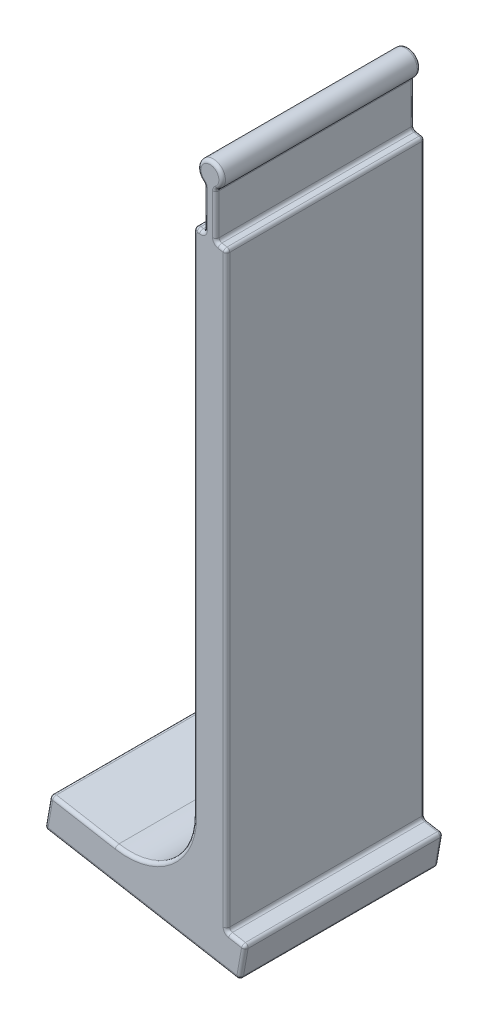
SolidWorks part; units mm, degrees
ref_plane "Alzado" through (0, 0, 0) normal (0, 0, 1) x (1, 0, 0)
ref_plane "Planta" through (0, 0, 0) normal (0, 1, 0) x (1, 0, 0)
ref_plane "Vista lateral" through (0, 0, 0) normal (1, 0, 0) x (0, 0, -1)
sketch "Croquis1" plane through (0, 0, 0) normal (0, 0, 1) x (1, 0, 0)
  line L0 (-0.9, 0) -> (0.9, 0)
  line L1 (-0.9, 0) -> (-0.9, -9.3)
  line L2 (0.9, 0) -> (0.9, -9.3)
  line L3 (-0.9, -9.3) -> (0.9, -9.3)
  line L16 (2.1527, -10.695) -> (-2.5, -9.8746)
  line L17 (2.1527, -10.695) -> (2.5, -8.7254)
  line L18 (-2.5, -9.8746) -> (-2.1527, -7.905)
  line L19 (2.5, -8.7254) -> (-2.1527, -7.905)
  line L20 (2.1527, -10.695) -> (-2.1527, -7.905) construction
  line L21 (-2.5, -9.8746) -> (2.5, -8.7254) construction
  line L22 (2.5, -8.7254) -> (-2.5, -8.7254)
  line L23 (2.5, -8.7254) -> (2.5, -100)
  line L24 (-2.5, -8.7254) -> (-2.5, -100)
  line L25 (2.5, -100) -> (-2.5, -100)
  line L30 (4.4899, -103.3303) -> (-5.3582, -101.5938)
  line L31 (4.4899, -103.3303) -> (5.3582, -98.4062)
  line L32 (-5.3582, -101.5938) -> (-4.4899, -96.6697)
  line L33 (5.3582, -98.4062) -> (-4.4899, -96.6697)
  line L34 (4.4899, -103.3303) -> (-4.4899, -96.6697) construction
  line L35 (-5.3582, -101.5938) -> (5.3582, -98.4062) construction
  line L36 (-4.4899, -96.6697) -> (-5.3582, -101.5938)
  line L37 (-4.4899, -96.6697) -> (-24.1861, -93.1968)
  line L38 (-5.3582, -101.5938) -> (-25.0543, -98.1208)
  line L39 (-24.1861, -93.1968) -> (-25.0543, -98.1208)
  line L40 (-2.1527, -7.905) -> (-2.3492, -7.8703)
  line L41 (-2.1527, -7.905) -> (-2.3035, -8.76)
  line L42 (-2.3492, -7.8703) -> (-2.5, -8.7254)
  line L43 (-2.3035, -8.76) -> (-2.5, -8.7254)
  circle A0 centre (0, 0) radius 1.85
  point P6 (0, 0)
  point P9 (0, -9.3)
  point P10 (0, -9.3)
  point P11 (0, -100)
  point P22 (0.1327, -23.7973)
  dimension "D2" = 3.7
  dimension "D1" = 9.3
  dimension "D3" = 1.8
  dimension "D4" = 2
  dimension "D5" = 10
  dimension "D6" = 5
  dimension "D7" = 10
  dimension "D8" = 5
  dimension "D9" = 10
  dimension "D10" = 100
  dimension "D11" = 20
extrude "Saliente-Extruir1" add sketch "Croquis1" along normal blind 30
fillet "Redondeo1" radius 10 1 edges at (-2.5, -97.0206, 15)
fillet "Redondeo2" radius 0.5 40 edges at (-0.9, -4.8711, 30) (-1.6246, -7.9981, 30) (0.9, -5.0298, 0) (1.7, -8.5843, 0) (2.5, -53.3138, 0) (3.9291, -98.1542, 0) (4.924, -100.8682, 0) (-10.2822, -100.7255, 0) (-24.6202, -95.6588, 0) (-2.5, -46.9142, 0) (-2.4246, -8.2979, 0) (-1.6246, -7.9981, 0) (-0.9, -4.8711, 0) (0, 1.85, 0) (-2.4246, -8.2979, 30) (0.9, -1.6163, 15) (0.9, -8.4433, 15) (2.5, -8.7254, 15) (2.5, -97.9023, 15) (5.3582, -98.4062, 15) (4.4899, -103.3303, 15) (-25.0543, -98.1208, 15) (-24.1861, -93.1968, 15) (-2.5, -46.9142, 30) (-2.5, -8.7254, 15) (-2.3492, -7.8703, 15) (-0.9, -8.1259, 15) (-0.9, -1.6163, 15) (-24.6202, -95.6588, 30) (-10.2822, -100.7255, 30) (-19.2113, -94.074, 0) (-19.2113, -94.074, 30) (-6.0721, -92.7635, 0) (-6.0721, -92.7635, 30) (0, 1.85, 30) (4.924, -100.8682, 30) (3.9291, -98.1542, 30) (2.5, -53.3138, 30) (1.7, -8.5843, 30) (0.9, -5.0298, 30)
